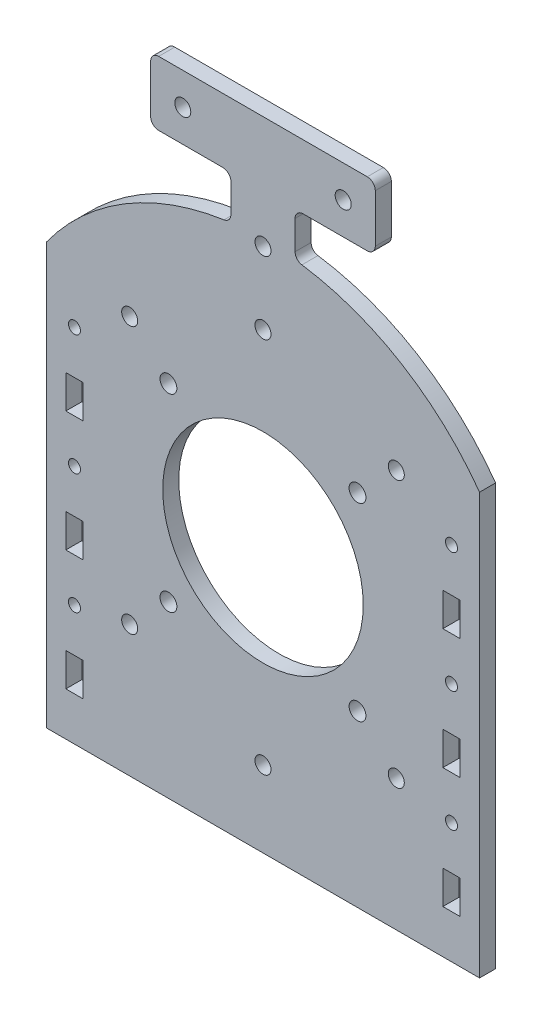
SolidWorks part; units mm, degrees
ref_plane "前视基准面" through (0, 0, 0) normal (0, 0, 1) x (1, 0, 0)
ref_plane "上视基准面" through (0, 0, 0) normal (0, 1, 0) x (1, 0, 0)
ref_plane "右视基准面" through (0, 0, 0) normal (1, 0, 0) x (0, 0, -1)
sketch "草图1" plane through (0, 0, 0) normal (0, 0, 1) x (1, 0, 0)
  line L0 (-47, 39) -> (-47, 36)
  line L1 (-47, 26.5) -> (-47, 18.5) construction
  line L3 (-49.15, 18.35) -> (-44.85, 18.35)
  line L4 (-49.15, 18.35) -> (-49.15, 26.65)
  line L5 (-49.15, 26.65) -> (-44.85, 26.65)
  line L6 (-44.85, 18.35) -> (-44.85, 26.65)
  line L7 (-49.15, 18.35) -> (-44.85, 26.65) construction
  line L8 (-49.15, 26.65) -> (-44.85, 18.35) construction
  line L20 (-44.85, -11.65) -> (-44.85, -3.35)
  line L21 (-49.15, -11.65) -> (-44.85, -11.65)
  line L22 (-49.15, -11.65) -> (-49.15, -3.35)
  line L23 (-49.15, -3.35) -> (-44.85, -3.35)
  line L24 (-44.85, -41.65) -> (-44.85, -33.35)
  line L25 (-49.15, -41.65) -> (-44.85, -41.65)
  line L26 (-49.15, -41.65) -> (-49.15, -33.35)
  line L27 (-49.15, -33.35) -> (-44.85, -33.35)
  line L29 (-54, 52.4) -> (-54, -52.5)
  line L32 (0, 71) -> (0, -44) construction
  line L33 (-23.57, 37.07) -> (-23.57, -10.07) construction
  line L34 (23.57, 37.07) -> (23.57, -10.07) construction
  line L35 (49.15, 26.65) -> (44.85, 18.35) construction
  line L36 (49.15, 18.35) -> (44.85, 26.65) construction
  line L37 (47, 26.5) -> (47, 18.5) construction
  line L38 (54, 52.4) -> (54, -52.5)
  line L39 (49.15, -33.35) -> (44.85, -33.35)
  line L40 (49.15, -41.65) -> (49.15, -33.35)
  line L41 (49.15, -41.65) -> (44.85, -41.65)
  line L42 (44.85, -41.65) -> (44.85, -33.35)
  line L43 (49.15, -3.35) -> (44.85, -3.35)
  line L44 (49.15, -11.65) -> (49.15, -3.35)
  line L45 (49.15, -11.65) -> (44.85, -11.65)
  line L46 (44.85, -11.65) -> (44.85, -3.35)
  line L47 (44.85, 18.35) -> (44.85, 26.65)
  line L48 (49.15, 26.65) -> (44.85, 26.65)
  line L49 (49.15, 18.35) -> (49.15, 26.65)
  line L50 (49.15, 18.35) -> (44.85, 18.35)
  line L51 (47, 39) -> (47, 36)
  line L52 (-54, 52.4) -> (54, 52.4) construction
  line L53 (54, -52.5) -> (-54, -52.5)
  line L54 (-47, 7.5) -> (-54, 7.5) construction
  line L55 (-47, 37.5) -> (-47, 22.5) construction
  line L56 (-47, 22.5) -> (-47, 7.5) construction
  line L57 (-47, 7.5) -> (-47, -22.5) construction
  line L58 (-49.15, 18.35) -> (-49.15, -3.35) construction
  line L59 (-49.15, -11.65) -> (-49.15, -33.35)
  line L60 (0, 78.5) -> (0, 84.5) construction
  line L61 (-28, 106.5) -> (28, 106.5)
  line L62 (28, 106.5) -> (28, 90.5)
  line L63 (28, 90.5) -> (8, 90.5)
  line L64 (8, 90.5) -> (8, 79.5697)
  line L65 (-28, 106.5) -> (-28, 90.5)
  line L66 (-28, 90.5) -> (-8, 90.5)
  line L67 (-8, 90.5) -> (-8, 79.5697)
  circle A0 centre (-47, 37.5) radius 1.5
  circle A4 centre (-47, 7.5) radius 1.5
  circle A5 centre (-47, -22.5) radius 1.5
  circle A7 centre (-23.57, 37.07) radius 2.1
  circle A10 centre (-23.57, -10.07) radius 2.1
  circle A11 centre (23.57, -10.07) radius 2.1
  circle A12 centre (23.57, 37.07) radius 2.1
  circle A13 centre (47, -22.5) radius 1.5
  circle A14 centre (47, 7.5) radius 1.5
  circle A15 centre (47, 37.5) radius 1.5
  circle A16 centre (0, 13.5) radius 25
  circle A17 centre (0, 13.5) radius 47 construction
  circle A18 centre (0, 60.5) radius 2
  arc A40 (-54, 52.4) -> (54, 52.4) centre (0, 13.5) cw construction
  circle A41 centre (33.234, 46.734) radius 2
  circle A42 centre (47, 13.5) radius 2 construction
  circle A43 centre (33.234, -19.734) radius 2
  circle A44 centre (0, -33.5) radius 2
  circle A45 centre (-33.234, -19.734) radius 2
  circle A46 centre (-47, 13.5) radius 2 construction
  circle A47 centre (-33.234, 46.734) radius 2
  circle A48 centre (0, 78.5) radius 2
  circle A50 centre (-20, 98.5) radius 2
  circle A51 centre (20, 98.5) radius 2
  arc A52 (-54, 52.4) -> (-8, 79.5697) centre (0, 13.5) cw
  arc A53 (8, 79.5697) -> (54, 52.4) centre (0, 13.5) cw
  point P6 (-47, 22.5)
  point P59 (47, 22.5)
  dimension "D3" = 4.2
  dimension "D6" = 23.57
  dimension "D8" = 15
  dimension "D10" = 65
  dimension "D11" = 94
  dimension "D14" = 30
  dimension "D16" = 4
  dimension "D27" = 50
  dimension "D1" = 8.3
  dimension "D2" = 4.3
  dimension "D4" = 4.85
  dimension "D5" = 8
  dimension "D7" = 47.14
  dimension "D9" = 30
  dimension "D12" = 24
  dimension "D13" = 15
  dimension "D15" = 30
  dimension "D17" = 20
  dimension "D18" = 20
  dimension "D19" = 20
  dimension "D20" = 20
  dimension "D21" = 8
  dimension "D22" = 8
  dimension "D23" = 8
  dimension "D24" = 8
  dimension "D25" = 8
  dimension "D26" = 8
extrude "凸台-拉伸1" add sketch "草图1" along normal blind 4
fillet "圆角1" radius 2 8 edges at (-8, 79.5697, 2) (8, 79.5697, 2) (-8, 90.5, 2) (8, 90.5, 2) (28, 90.5, 2) (28, 106.5, 2) (-28, 90.5, 2) (-28, 106.5, 2)
